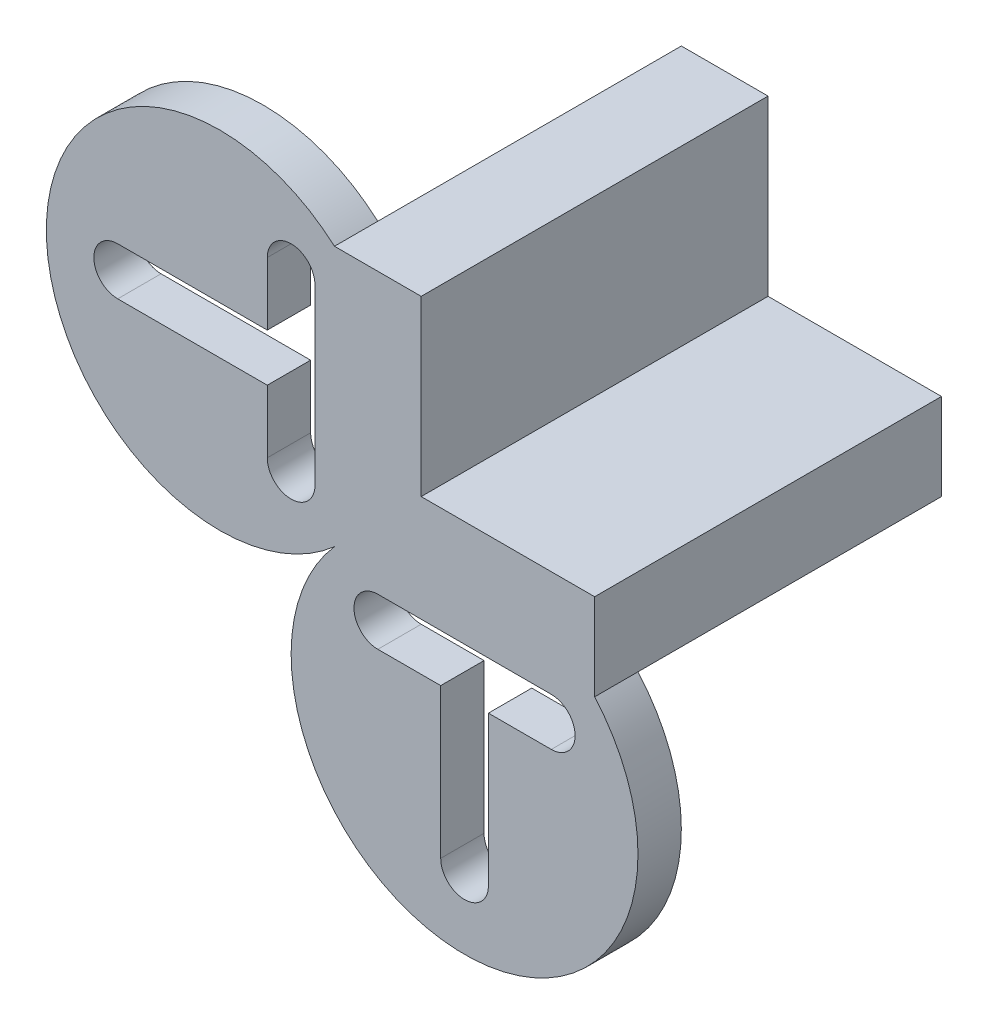
SolidWorks part; units mm, degrees
ref_plane "Front Plane" through (0, 0, 0) normal (0, 0, 1) x (1, 0, 0)
ref_plane "Top Plane" through (0, 0, 0) normal (0, 1, 0) x (1, 0, 0)
ref_plane "Right Plane" through (0, 0, 0) normal (1, 0, 0) x (0, 0, -1)
sketch "Sketch1" plane through (0, 0, 0) normal (0, 0, 1) x (1, 0, 0)
  line L0 (0, 20) -> (-10, 20)
  line L1 (0, 167) -> (0, 0) construction
  line L2 (-10, 20) -> (-10, -10)
  line L3 (-10, -10) -> (20, -10)
  line L4 (20, -10) -> (20, 0)
  line L5 (0, 0) -> (178, 0) construction
  line L6 (20, 0) -> (0, 0)
  line L7 (0, 0) -> (0, 20)
  dimension "D1" = 10
  dimension "D2" = 10
  dimension "D3" = 20
  dimension "D4" = 20
extrude "Walls" add sketch "Sketch1" against normal blind 40
sketch "Sketch2" plane through (0, 0, 0) normal (0, 0, 1) x (1, 0, 0)
  line L0 (-10, 20) -> (-10, -10)
  line L2 (20, -10) -> (-10, -10)
  arc A1 (-10, -10) -> (-10, 20) centre (-23.2288, 5) cw
  arc A2 (20, -10) -> (-10, -10) centre (5, -23.2288) cw
  dimension "D1" = 20
extrude "Tabs" add sketch "Sketch2" against normal blind 5
sketch "Sketch3" plane through (0, 0, -5) normal (0, 0, -1) x (-1, 0, 0)
  line L0 (12.25, -5) -> (12.25, 15)
  line L3 (5, -17.75) -> (-2.25, -17.75)
  line L5 (10, 20) -> (10, -10) construction
  line L6 (-7.75, -17.75) -> (-15, -17.75)
  line L9 (17.75, -5) -> (17.75, 2.25)
  line L11 (17.75, 2.25) -> (35, 2.25)
  line L14 (-15, -12.25) -> (5, -12.25)
  line L15 (10, -10) -> (-20, -10) construction
  line L16 (-2.25, -17.75) -> (-2.25, -35)
  line L17 (-7.75, -17.75) -> (-7.75, -35)
  line L18 (35, 7.75) -> (17.75, 7.75)
  line L19 (17.75, 7.75) -> (17.75, 15)
  arc A8 (-2.25, -35) -> (-7.75, -35) centre (-5, -35) cw
  arc A9 (5, -17.75) -> (5, -12.25) centre (5, -15) ccw
  arc A10 (-15, -12.25) -> (-15, -17.75) centre (-15, -15) ccw
  arc A12 (12.25, 15) -> (17.75, 15) centre (15, 15) cw
  arc A13 (12.25, -5) -> (17.75, -5) centre (15, -5) ccw
  arc A14 (35, 2.25) -> (35, 7.75) centre (35, 5) ccw
  dimension "D3" = 2.25
  dimension "D5" = 2.75
  dimension "D2" = 5.5
  dimension "D4" = 5
  dimension "D6" = 20
  dimension "D7" = 17.25
  dimension "D8" = 7.25
  dimension "D9" = 2.25
  dimension "D10" = 5
  dimension "D11" = 5
extrude "Holes" cut sketch "Sketch3" against normal through all
